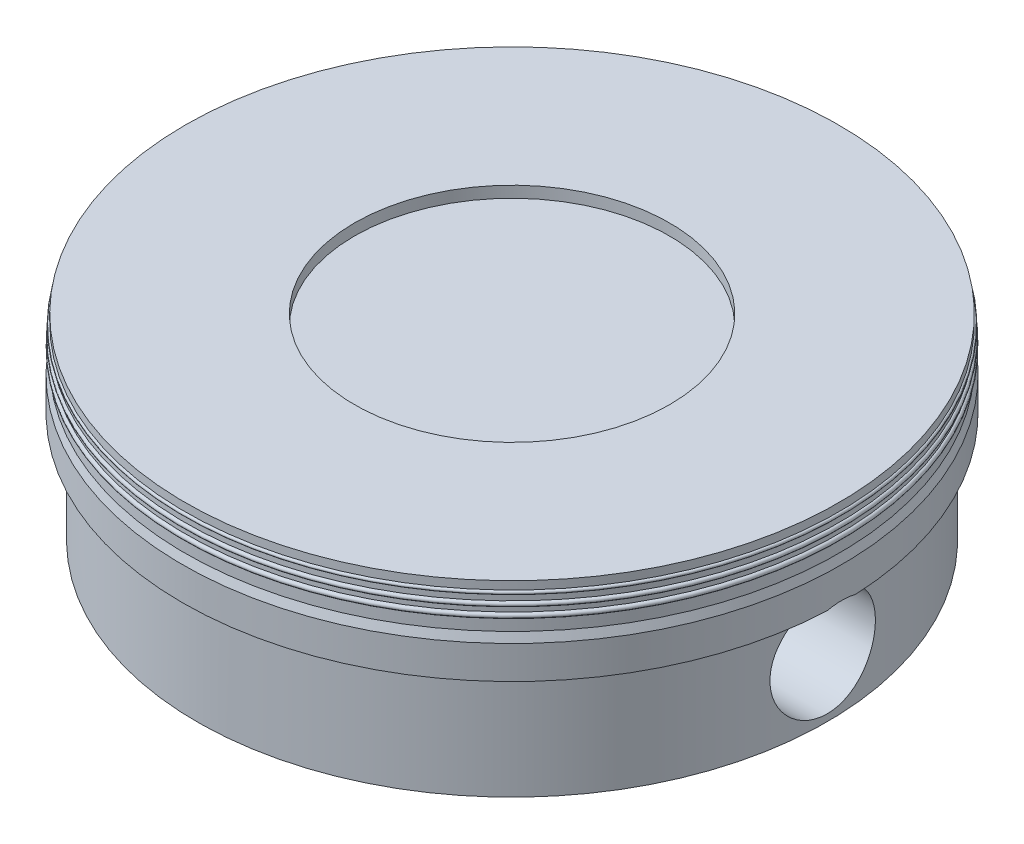
SolidWorks part; units mm, degrees
ref_plane "Front Plane" through (0, 0, 0) normal (0, 0, 1) x (1, 0, 0)
ref_plane "Top Plane" through (0, 0, 0) normal (0, 1, 0) x (1, 0, 0)
ref_plane "Right Plane" through (0, 0, 0) normal (1, 0, 0) x (0, 0, -1)
sketch "Sketch1" plane through (0, 0, 0) normal (0, 0, 1) x (1, 0, 0)
  line L0 (0, 76.2) -> (0, 0) construction
  line L1 (0, 0) -> (127, 0) construction
  line L2 (121.412, 0) -> (87.122, 0)
  line L3 (87.122, 0) -> (87.122, 49.022)
  line L4 (87.122, 49.022) -> (106.68, 49.022)
  line L5 (106.68, 49.022) -> (106.68, 59.182)
  line L6 (106.68, 59.182) -> (0, 59.182)
  line L7 (0, 59.182) -> (0, 71.12)
  line L8 (0, 71.12) -> (60.706, 71.12)
  line L9 (60.706, 71.12) -> (60.706, 75.4888)
  line L10 (60.706, 75.4888) -> (125.984, 75.4888)
  line L11 (125.984, 75.4888) -> (125.984, 72.3655)
  line L12 (125.984, 58.5416) -> (127, 55.245)
  line L13 (127, 55.245) -> (127, 42.545)
  line L14 (127, 42.545) -> (121.412, 42.545)
  line L15 (121.412, 42.545) -> (121.412, 0)
  line L16 (125.984, 66.9756) -> (125.984, 65.0433)
  line L17 (125.984, 70.9921) -> (125.984, 68.762)
  line L18 (125.984, 63.0743) -> (125.984, 58.5416)
  arc A0 (125.984, 70.9921) -> (125.984, 72.3655) centre (125.984, 71.6788) ccw
  arc A1 (125.984, 66.9756) -> (125.984, 68.762) centre (125.984, 67.8688) ccw
  arc A2 (125.984, 63.0743) -> (125.984, 65.0433) centre (125.984, 64.0588) ccw
  dimension "D1" = 127
  dimension "D2" = 76.2
  dimension "D3" = 125.984
  dimension "D4" = 1.016
  dimension "D5" = 5.588
  dimension "D6" = 42.545
  dimension "D7" = 34.29
  dimension "D8" = 49.022
  dimension "D9" = 10.16
  dimension "D10" = 65.278
  dimension "D11" = 11.938
  dimension "D12" = 4.3688
  dimension "D13" = 106.68
  dimension "D14" = 3.81
  dimension "D15" = 3.81
  dimension "D16" = 3.81
  dimension "D17" = 12.7
  dimension "D18" = 3.2966
revolve "Revolve1" add sketch "Sketch1" angle 360 about L0
sketch "Sketch2" plane through (0, 0, 0) normal (0, -1, 0) x (1, 0, 0)
  line L1 (0, 0) -> (-87.122, 0) construction
  line L2 (-44.45, 74.9296) -> (-44.45, -74.9296)
  line L3 (44.45, 74.9296) -> (44.45, -74.9296)
  circle A0 centre (0, 0) radius 87.122 construction
  arc A1 (-44.45, 74.9296) -> (-44.45, -74.9296) centre (0, 0) ccw
  arc A2 (44.45, -74.9296) -> (44.45, 74.9296) centre (0, 0) ccw
  dimension "D1" = 88.9
extrude "Boss-Extrude2" add sketch "Sketch2" against normal blind 63.5
sketch "Sketch3" plane through (0, 0, 0) normal (1, 0, 0) x (0, 0, -1)
  circle A0 centre (0, 22.987) radius 20.32
  point P2 (0, 0)
  dimension "D1" = 40.64
  dimension "D2" = 22.987
extrude "Cut-Extrude1" cut sketch "Sketch3" against normal through all both and the other way through all
